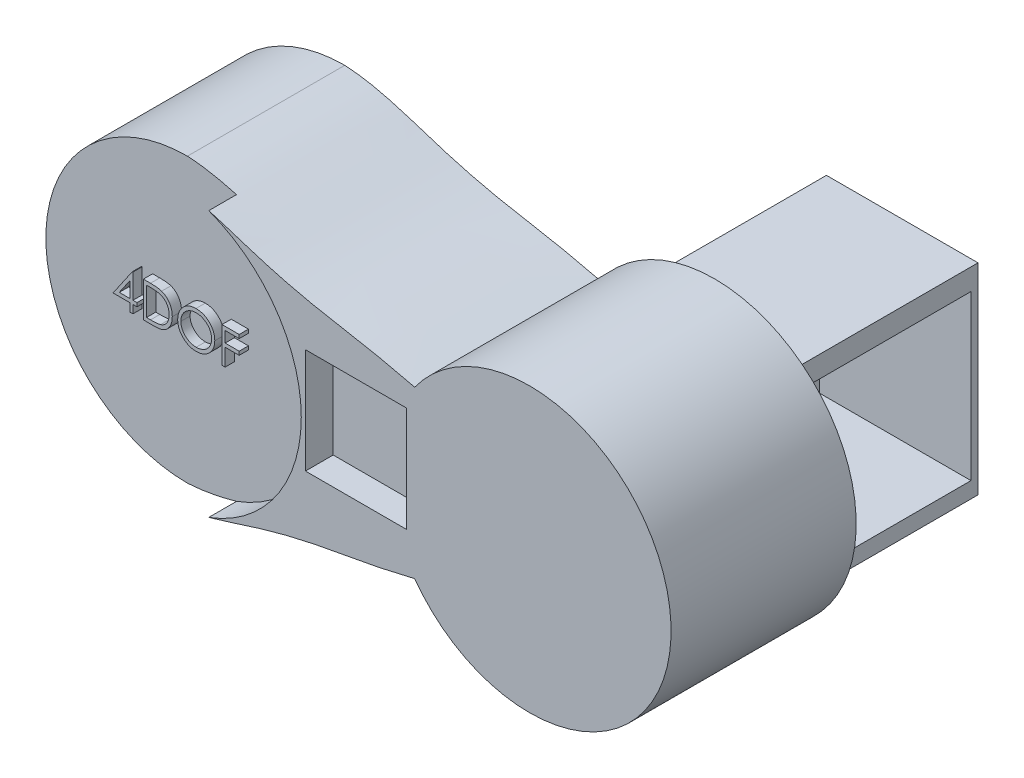
SolidWorks part; units mm, degrees
ref_plane "Front Plane" through (0, 0, 0) normal (0, 0, 1) x (1, 0, 0)
ref_plane "Top Plane" through (0, 0, 0) normal (0, 1, 0) x (1, 0, 0)
ref_plane "Right Plane" through (0, 0, 0) normal (1, 0, 0) x (0, 0, -1)
sketch "Sketch1" plane through (0, 0, 0) normal (0, 0, 1) x (1, 0, 0)
  line L0 (276.2628, 0) -> (-236.0406, 0) construction
  arc A0 (0, 76.495) -> (0, -76.495) centre (0, 0) ccw
  arc A2 (137.7598, -44.7938) -> (137.7598, 44.7938) centre (199.7678, 0) ccw
  spline S0 degree 3 poles (0, 76.495) (18.8458, 75.5336) (46.0745, 64.6211) (86.2325, 54.667) (114.48, 50.4671) (132.0289, 46.0459) (137.7598, 44.7938) knots 0 0 0 0 0.27322 0.429577 0.608078 0.694264 0.694264 0.694264 0.694264
  spline S1 degree 3 poles (0, -76.495) (18.8458, -75.5336) (46.0745, -64.6211) (86.2325, -54.667) (114.48, -50.4671) (132.0289, -46.0459) (137.7598, -44.7938) knots 0 0 0 0 0.27322 0.429577 0.608078 0.694264 0.694264 0.694264 0.694264
  dimension "D1" = 152.99
  dimension "D3" = 152.99
extrude "Boss-Extrude1" add sketch "Sketch1" along normal blind 100
sketch "Sketch2" plane through (0, 0, 0) normal (0, 0, -1) x (-1, 0, 0)
  line L0 (43.7942, 54.2507) -> (42.685, -31.7421)
  line L1 (42.685, -31.7421) -> (-43.3079, -30.6329)
  line L2 (-43.3079, -30.6329) -> (-42.1987, 55.3599)
  line L3 (-42.1987, 55.3599) -> (43.7942, 54.2507)
extrude "Cut-Extrude1" cut sketch "Sketch2" against normal blind 39
sketch "Sketch3" plane through (0, 0, 39) normal (0, 0, -1) x (-1, 0, 0)
  line L0 (6.1366, 14.5425) -> (10.0319, 14.6375)
  line L1 (10.0319, 14.6375) -> (10.1538, 9.639)
  line L2 (10.1538, 9.639) -> (6.2585, 9.544)
  arc A0 (6.1366, 14.5425) -> (6.2585, 9.544) centre (0.1583, 11.896) ccw
extrude "Cut-Extrude2" cut sketch "Sketch3" against normal blind 39
sketch "Sketch4" plane through (0, 0, 100) normal (0, 0, 1) x (1, 0, 0)
  circle A0 centre (0, 0) radius 76.495
extrude "Cut-Extrude3" cut sketch "Sketch4" against normal blind 15
sketch "Sketch5" plane through (0, 0, 100) normal (0, 0, 1) x (1, 0, 0)
  line L1 (78.7377, 32.8305) -> (133.376, 32.8305)
  line L2 (78.7377, 32.8305) -> (78.7377, -23.9589)
  line L3 (78.7377, -23.9589) -> (133.376, -23.9589)
  line L4 (133.376, 32.8305) -> (133.376, -23.9589)
extrude "Cut-Extrude4" cut sketch "Sketch5" against normal blind 15
fillet "Fillet4" radius 10 1 edges at (133.376, 4.4358, 85)
sketch "Sketch6" plane through (0, 0, 39) normal (0, 0, -1) x (-1, 0, 0)
  circle A0 centre (0, 0) radius 74.9952
extrude "Cut-Extrude5" cut sketch "Sketch6" along normal up to vertex (39 mm away)
sketch "Sketch7" plane through (0, 0, 85) normal (0, 0, 1) x (1, 0, 0)
  text T0 "4DOF" font "Century Gothic" height in points 72
extrude "Boss-Extrude2" add sketch "Sketch7" along normal blind 5
sketch "Sketch8" plane through (0, 0, 0) normal (0, 0, -1) x (-1, 0, 0)
  line L1 (-247.0639, 60.1213) -> (-165.1948, 60.1213)
  line L2 (-247.0639, 60.1213) -> (-247.0639, -48.4648)
  line L3 (-247.0639, -48.4648) -> (-165.1948, -48.4648)
  line L4 (-165.1948, 60.1213) -> (-165.1948, -48.4648)
  arc A0 (-137.7598, 44.7938) -> (-137.7598, -44.7938) centre (-199.7678, 0) ccw construction
extrude "Boss-Extrude4" add sketch "Sketch8" along normal blind 95
sketch "Sketch10" plane through (165.1948, 0, 0) normal (-1, 0, 0) x (0, 0, 1)
  line L1 (-91.2098, 48.5832) -> (-1.9394, 48.5832)
  line L2 (-91.2098, 48.5832) -> (-91.2098, -39.8693)
  line L3 (-91.2098, -39.8693) -> (-1.9394, -39.8693)
  line L4 (-1.9394, 48.5832) -> (-1.9394, -39.8693)
extrude "Cut-Extrude6" cut sketch "Sketch10" against normal blind 95
sketch "Sketch11" plane through (0, 0, -95) normal (0, 0, -1) x (-1, 0, 0)
  circle A0 centre (-208.3845, 6.0942) radius 5
  circle A1 centre (-208.3845, 35.7604) radius 5
  circle A2 centre (-208.3845, -23.2715) radius 5
extrude "Boss-Extrude5" add sketch "Sketch11" along normal blind 19
fillet "Fillet9" radius 2 3 edges at (203.3845, -23.2715, -114) (203.3845, 6.0942, -114) (203.3845, 35.7604, -114)
sketch "Sketch12" plane through (165.1948, 0, 0) normal (-1, 0, 0) x (0, 0, 1)
  line L1 (-91.2098, 48.5832) -> (-1.9394, 48.5832)
  line L2 (-91.2098, 48.5832) -> (-91.2098, -39.8693)
  line L3 (-91.2098, -39.8693) -> (-1.9394, -39.8693)
  line L4 (-1.9394, 48.5832) -> (-1.9394, -39.8693)
extrude "Boss-Extrude6" add sketch "Sketch12" along normal blind 5 separate body
